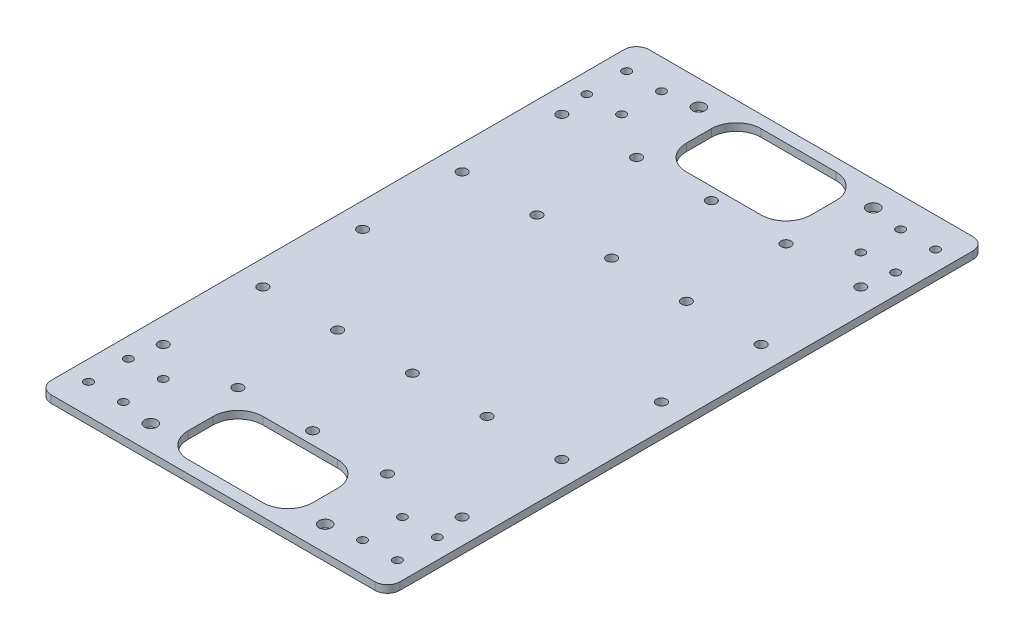
SolidWorks part; units mm, degrees
ref_plane "前视基准面" through (0, 0, 0) normal (0, 0, 1) x (1, 0, 0)
ref_plane "上视基准面" through (0, 0, 0) normal (0, 1, 0) x (1, 0, 0)
ref_plane "右视基准面" through (0, 0, 0) normal (1, 0, 0) x (0, 0, -1)
other "Configuration Table"
sketch "草图1" plane through (0, 0, 0) normal (0, 1, 0) x (1, 0, 0)
  line L0 (0, 120) -> (0, -49880) construction
  line L5 (-100, -120) -> (100, 120) construction
  line L6 (-100, 120) -> (100, -120) construction
  line L7 (-100, 120) -> (-70, 120)
  line L8 (-100, 120) -> (-100, 80)
  line L9 (-95, 80) -> (-75, 80)
  line L10 (-70, 115) -> (-70, 85)
  line L11 (-65, 0) -> (49935, 0) construction
  line L12 (-70, 120) -> (-70, 113)
  line L13 (-70, 113) -> (-70, 87)
  line L14 (-70, 87) -> (-70, 80)
  line L15 (-70, 113) -> (-40, 113)
  line L16 (-40, 113) -> (-40, 87)
  line L17 (-40, 87) -> (-70, 87)
  line L18 (-70, 113) -> (-70, 108)
  line L19 (-70, 87) -> (-70, 92)
  line L20 (-40, 87) -> (-48, 87)
  line L21 (-48, 87) -> (-48, 92)
  line L22 (-48, 92) -> (-40, 92)
  line L23 (-70, 92) -> (-62, 92)
  line L24 (-62, 92) -> (-62, 87)
  line L25 (-70, 100) -> (-40, 100) construction
  line L26 (0, 120) -> (0, 0)
  line L27 (0, 0) -> (-100, 0)
  line L28 (-70, 80) -> (0, 80)
  line L29 (95, 80) -> (75, 80)
  line L30 (70, 115) -> (70, 85)
  line L31 (95, -80) -> (75, -80)
  line L32 (70, -115) -> (70, -85)
  line L33 (-70, -115) -> (-70, -85)
  line L34 (-95, -80) -> (-75, -80)
  line L35 (0, 120) -> (0, 100)
  line L36 (0, 100) -> (-25, 100)
  line L37 (-25, 95) -> (-25, 105)
  line L38 (-25, 100) -> (-25, 85)
  line L39 (-25, 85) -> (-5, 85)
  line L40 (-15, 115) -> (-5, 115)
  line L41 (-5, 115) -> (-5, 85)
  line L42 (5, 115) -> (5, 85)
  line L43 (25, 100) -> (25, 95)
  line L44 (15, 85) -> (5, 85)
  line L45 (15, 115) -> (5, 115)
  line L46 (25, 100) -> (25, 105)
  line L47 (15, -85) -> (5, -85)
  line L48 (25, -100) -> (25, -95)
  line L49 (25, -100) -> (25, -105)
  line L50 (15, -115) -> (5, -115)
  line L51 (5, -115) -> (5, -85)
  line L52 (-25, -100) -> (-25, -105)
  line L53 (-25, -100) -> (-25, -95)
  line L54 (-15, -85) -> (-5, -85)
  line L55 (-5, -115) -> (-5, -85)
  line L56 (-15, -115) -> (-5, -115)
  line L57 (-100, 0) -> (-90, 0)
  line L58 (0, 120) -> (0, 100)
  line L59 (0, 120) -> (0, 110)
  line L60 (-100, 75) -> (-100, -75)
  line L61 (-65, -120) -> (65, -120)
  line L62 (100, 75) -> (100, -75)
  line L63 (-65, 120) -> (65, 120)
  line L64 (-5, -85) -> (5, -85)
  line L65 (-5, -115) -> (5, -115)
  line L66 (-5, 115) -> (5, 115)
  line L67 (-15, 85) -> (5, 85)
  line L68 (-70, 85) -> (-70, -85)
  line L69 (70, 85) -> (70, -85)
  circle A0 centre (-62, 92) radius 1.7
  circle A1 centre (-48, 92) radius 1.7
  circle A2 centre (-48, 108) radius 1.7
  circle A3 centre (-62, 108) radius 1.7
  circle A4 centre (48, 108) radius 1.7
  circle A5 centre (48, 92) radius 1.7
  circle A6 centre (62, 92) radius 1.7
  circle A7 centre (62, 108) radius 1.7
  circle A8 centre (62, -108) radius 1.7
  circle A9 centre (62, -92) radius 1.7
  circle A10 centre (48, -92) radius 1.7
  circle A11 centre (48, -108) radius 1.7
  circle A12 centre (-48, -92) radius 1.7
  circle A13 centre (-62, -92) radius 1.7
  circle A14 centre (-48, -108) radius 1.7
  circle A15 centre (-62, -108) radius 1.7
  circle A16 centre (-90, 0) radius 2.5
  circle A17 centre (-90, 50) radius 2.5
  circle A18 centre (-90, -50) radius 2.5
  circle A19 centre (90, -50) radius 2.5
  circle A20 centre (90, 0) radius 2.5
  circle A21 centre (90, 50) radius 2.5
  circle A22 centre (0, 110) radius 2.5
  circle A23 centre (35, 110) radius 2.5
  circle A24 centre (-35, 110) radius 2.5
  circle A25 centre (35, -110) radius 2.5
  circle A26 centre (0, -110) radius 2.5
  circle A27 centre (-35, -110) radius 2.5
  arc A28 (-95, -80) -> (-100, -75) centre (-95, -75) cw
  arc A29 (-70, -85) -> (-75, -80) centre (-75, -85) ccw
  arc A30 (-65, -120) -> (-70, -115) centre (-65, -115) cw
  arc A31 (70, -115) -> (65, -120) centre (65, -115) cw
  arc A32 (70, 85) -> (75, 80) centre (75, 85) ccw
  arc A33 (75, -80) -> (70, -85) centre (75, -85) ccw
  arc A34 (95, -80) -> (100, -75) centre (95, -75) ccw
  arc A35 (95, 80) -> (100, 75) centre (95, 75) cw
  arc A36 (70, 115) -> (65, 120) centre (65, 115) ccw
  arc A37 (-70, 115) -> (-65, 120) centre (-65, 115) cw
  arc A38 (-70, 85) -> (-75, 80) centre (-75, 85) cw
  arc A39 (-95, 80) -> (-100, 75) centre (-95, 75) ccw
  arc A40 (15, -85) -> (25, -95) centre (15, -95) cw
  arc A41 (25, -105) -> (15, -115) centre (15, -105) cw
  arc A42 (-25, -105) -> (-15, -115) centre (-15, -105) ccw
  arc A43 (-25, -95) -> (-15, -85) centre (-15, -95) cw
  arc A44 (15, 85) -> (25, 95) centre (15, 95) ccw
  arc A45 (25, 105) -> (15, 115) centre (15, 105) ccw
  arc A46 (-15, 115) -> (-25, 105) centre (-15, 105) ccw
  arc A47 (-25, 95) -> (-15, 85) centre (-15, 95) ccw
  point P0 (0, 0)
  point P15 (-100, -80)
  point P119 (-70, -80)
  point P122 (-70, -120)
  point P125 (70, -120)
  point P128 (70, 80)
  point P131 (70, -80)
  point P134 (100, -80)
  point P137 (100, 80)
  point P140 (70, 120)
  point P152 (25, -85)
  point P155 (25, -115)
  point P158 (-25, -115)
  point P161 (-25, -85)
  point P164 (25, 85)
  point P167 (25, 115)
  point P170 (-25, 115)
  dimension "D12" = 3.4
  dimension "D13" = 3.4
  dimension "D19" = 5
  dimension "D23" = 5
  dimension "D25" = 5
  dimension "D26" = 5
  dimension "D27" = 10
  dimension "D1" = 200
  dimension "D2" = 240
  dimension "D3" = 30
  dimension "D4" = 40
  dimension "D5" = 7
  dimension "D6" = 7
  dimension "D7" = 30
  dimension "D8" = 5
  dimension "D9" = 5
  dimension "D10" = 8
  dimension "D11" = 8
  dimension "D18" = 10
  dimension "D21" = 20
  dimension "D22" = 10
  dimension "D20" = 2
  dimension "D24" = 2
extrude "凸台-拉伸1" add sketch "草图1" along normal blind 3 contours A45 L46 L43 A44 L44 L67 L26 L27 L68 L33 A30 L61 A31 L32 L69 L30 A36 L63 L66 L45 A25 A15 A14 A12 A8 A7 A5 A4 A6 A9 A10 A11 A13 A23 | L28 L68 L27 L26 | A46 L40 L66 L26 L63 A37 L10 L15 L16 L17 L14 L28 L67 L39 L38 L37 A24 | A47 L38 L39 | A1 L22 L16 L15 L10 L13 L23 A0 L24 L17 L21 A2 A3 | A0 L23 L10 L17 L24 | A1 L21 L17 L16 L22
sketch "草图2" plane through (0, 3, 0) normal (0, 1, 0) x (1, 0, 0)
  line L0 (-1000, 0) -> (49000, 0) construction
  line L1 (0, -1000) -> (0, 49000) construction
  line L2 (-70, 0) -> (-60, 0)
  line L3 (-70, 115) -> (-70, -115) construction
  line L4 (70, 0) -> (60, 0)
  circle A0 centre (-60, 0) radius 2
  circle A1 centre (-60, 40) radius 2
  circle A2 centre (-60, 80) radius 2
  circle A3 centre (-60, -80) radius 2
  circle A4 centre (-60, -40) radius 2
  circle A5 centre (-30, 40) radius 2
  circle A6 centre (-30, 80) radius 2
  circle A7 centre (-30, -40) radius 2
  circle A8 centre (-30, -80) radius 2
  circle A9 centre (30, -80) radius 2
  circle A10 centre (30, -40) radius 2
  circle A11 centre (30, 80) radius 2
  circle A12 centre (30, 40) radius 2
  circle A13 centre (60, -40) radius 2
  circle A14 centre (60, -80) radius 2
  circle A15 centre (60, 80) radius 2
  circle A16 centre (60, 40) radius 2
  circle A17 centre (60, 0) radius 2
  circle A18 centre (0, -40) radius 2
  circle A19 centre (0, -80) radius 2
  circle A20 centre (0, 80) radius 2
  circle A21 centre (0, 40) radius 2
  dimension "D2" = 4
  dimension "D5" = 4
  dimension "D6" = 4
  dimension "D1" = 10
  dimension "D3" = 3
  dimension "D4" = 2
extrude "切除-拉伸1" cut sketch "草图2" against normal blind 3
